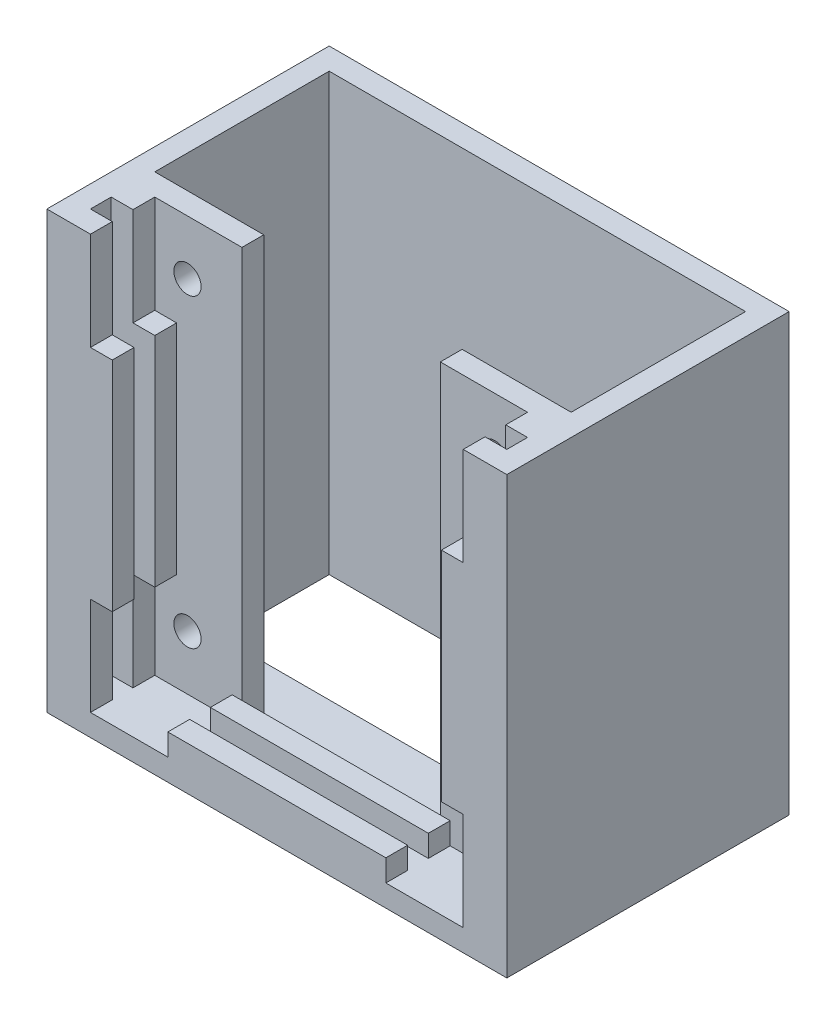
SolidWorks part; units mm, degrees
ref_plane "Front Plane" through (0, 0, 0) normal (0, 0, 1) x (1, 0, 0)
ref_plane "Top Plane" through (0, 0, 0) normal (0, 1, 0) x (1, 0, 0)
ref_plane "Right Plane" through (0, 0, 0) normal (1, 0, 0) x (0, 0, -1)
sketch "Sketch1" plane through (0, 0, 0) normal (0, 1, 0) x (1, 0, 0)
  line L5 (-62.899, -24.1935) -> (-24.699, -24.1935)
  line L6 (-62.899, -24.1935) -> (-62.899, -26.0935)
  line L7 (-62.899, -26.0935) -> (-24.699, -26.0935)
  line L8 (-24.699, -24.1935) -> (-24.699, -26.0935)
  line L9 (-60.899, -22.1935) -> (-26.699, -22.1935)
  line L10 (-60.899, -22.1935) -> (-60.899, -28.0935)
  line L11 (-60.899, -28.0935) -> (-26.699, -28.0935)
  line L12 (-26.699, -22.1935) -> (-26.699, -28.0935)
  line L13 (-64.899, -22.1935) -> (-22.699, -22.1935)
  line L14 (-64.899, -22.1935) -> (-64.899, -28.0935)
  line L15 (-64.899, -28.0935) -> (-22.699, -28.0935)
  line L16 (-22.699, -22.1935) -> (-22.699, -28.0935)
  point P8 (-24.699, -25.1435)
  dimension "D1" = 38.2
  dimension "D2" = 1.9
  dimension "D3" = 2
  dimension "D4" = 2
  dimension "D5" = 2
  dimension "D6" = 2
  dimension "D7" = 2
  dimension "D8" = 2
  dimension "D9" = 2
  dimension "D10" = 2
extrude "Boss-Extrude1" add sketch "Sketch1" along normal blind 38 contours L14 L15 L10 L7 L6 L5 L13 | L16 L13 L12 L5 L8 L7 L15
sketch "Sketch2" plane through (0, 0, 0) normal (0, 1, 0) x (1, 0, 0)
  line L1 (-64.899, -28.0935) -> (-22.699, -28.0935)
  line L2 (-64.899, -28.0935) -> (-64.899, -22.1935)
  line L3 (-64.899, -22.1935) -> (-22.699, -22.1935)
  line L4 (-22.699, -28.0935) -> (-22.699, -22.1935)
  dimension "D1" = 42.2
  dimension "D2" = 5.9
extrude "Boss-Extrude2" add sketch "Sketch2" against normal blind 2
sketch "Sketch3" plane through (0, 0, 22.1935) normal (0, 0, -1) x (-1, 0, 0)
  line L1 (22.699, 38) -> (64.899, 38)
  line L2 (22.699, 38) -> (22.699, -2)
  line L3 (22.699, -2) -> (64.899, -2)
  line L4 (64.899, 38) -> (64.899, -2)
  line L9 (24.699, 38) -> (62.899, 38)
  line L10 (24.699, 38) -> (24.699, 0)
  line L11 (24.699, 0) -> (62.899, 0)
  line L12 (62.899, 38) -> (62.899, 0)
  line M6 (60.899, 38) -> (60.899, 0)
  line M7 (60.899, 0) -> (26.699, 0)
  line M8 (26.699, 0) -> (26.699, 38)
  line M9 (26.699, 38) -> (22.699, 38)
  line M10 (22.699, 38) -> (22.699, -2)
  line M11 (22.699, -2) -> (64.899, -2)
  line M12 (64.899, -2) -> (64.899, 38)
  line M13 (64.899, 38) -> (60.899, 38)
  dimension "D3" = 2
  dimension "D4" = 2
  dimension "D5" = 2
  dimension "D1" = 42.2
  dimension "D2" = 40
extrude "Boss-Extrude3" add sketch "Sketch3" along normal blind 18 contours M13 M6 M7 M8 M9 M10 M11 M12
sketch "Sketch4" plane through (0, 0, 4.1935) normal (0, 0, -1) x (-1, 0, 0)
  line L1 (22.699, 38) -> (64.899, 38)
  line L2 (22.699, 38) -> (22.699, -2)
  line L3 (22.699, -2) -> (64.899, -2)
  line L4 (64.899, 38) -> (64.899, -2)
extrude "Boss-Extrude4" add sketch "Sketch4" along normal blind 2
sketch "Sketch5" plane through (0, 0, 0) normal (0, 1, 0) x (1, 0, 0)
  line L13 (-60.899, -28.0935) -> (-26.699, -28.0935)
  line L14 (-60.899, -28.0935) -> (-60.899, -4.1935)
  line L15 (-26.699, -28.0935) -> (-26.699, -4.1935)
  line L16 (-60.899, -4.1935) -> (-26.699, -4.1935)
  line L18 (-60.899, -16.1435) -> (-26.699, -16.1435)
  line L20 (-62.899, -4.1935) -> (-60.899, -4.1935)
  line L21 (-62.899, -4.1935) -> (-62.899, -16.1435)
  line L22 (-62.899, -16.1435) -> (-60.899, -16.1435)
  line L23 (-60.899, -4.1935) -> (-60.899, -16.1435)
  line L24 (-26.699, -16.1435) -> (-24.699, -16.1435)
  line L25 (-26.699, -16.1435) -> (-26.699, -4.1935)
  line L26 (-26.699, -4.1935) -> (-24.699, -4.1935)
  line L27 (-24.699, -16.1435) -> (-24.699, -4.1935)
  dimension "D1" = 34.2
  dimension "D2" = 23.9
extrude "Cut-Extrude1" cut sketch "Sketch5" against normal through all
sketch "Sketch6" plane through (-60.899, 0, 0) normal (1, 0, 0) x (0, 0, -1)
  line L0 (-28.0935, 19) -> (-22.1935, 19)
  line L1 (-28.0935, 38) -> (-28.0935, 0) construction
  line L2 (-22.1935, 38) -> (-22.1935, 0) construction
  line L4 (-28.0935, 9) -> (-22.1935, 9)
  line L5 (-28.0935, 9) -> (-28.0935, 29)
  line L6 (-28.0935, 29) -> (-22.1935, 29)
  line L7 (-22.1935, 9) -> (-22.1935, 29)
  line L8 (-28.0935, 9) -> (-22.1935, 29) construction
  line L9 (-28.0935, 29) -> (-22.1935, 9) construction
  line L14 (-26.0935, 38) -> (-26.0935, 0) construction
  line L15 (-24.1935, 29) -> (-26.0935, 29)
  line L16 (-24.1935, 29) -> (-24.1935, 9)
  line L17 (-24.1935, 9) -> (-26.0935, 9)
  line L18 (-26.0935, 29) -> (-26.0935, 9)
  line L19 (-24.1935, 29) -> (-26.0935, 9) construction
  line L20 (-24.1935, 9) -> (-26.0935, 29) construction
  point P6 (-25.1435, 19)
  point P11 (-25.1435, 19)
  point P12 (-25.1435, 19)
  line M12 (-26.0935, 0) -> (-26.0935, 38)
  line M14 (-28.0935, 38) -> (-28.0935, 0)
  dimension "D1" = 20
  dimension "D2" = 20
  dimension "D3" = 1.9
extrude "Boss-Extrude5" add sketch "Sketch6" along normal blind 2 contours L6 L0 M14 M12 | L6 L16 L0 L7 | L4 L0 M14 M12 | L0 L16 L4 L7
sketch "Sketch7" plane through (-26.699, 0, 0) normal (-1, 0, 0) x (0, 0, 1)
  line L0 (28.0935, 19) -> (22.1935, 19)
  line L1 (28.0935, 38) -> (28.0935, 0) construction
  line L2 (22.1935, 38) -> (22.1935, 0) construction
  line L3 (24.1935, 38) -> (24.1935, 0) construction
  line L4 (28.0935, 29) -> (22.1935, 29)
  line L5 (28.0935, 29) -> (28.0935, 9)
  line L6 (28.0935, 9) -> (22.1935, 9)
  line L7 (22.1935, 29) -> (22.1935, 9)
  line L8 (28.0935, 29) -> (22.1935, 9) construction
  line L9 (28.0935, 9) -> (22.1935, 29) construction
  line L10 (26.0935, 9) -> (24.1935, 9)
  line L11 (26.0935, 9) -> (26.0935, 29)
  line L12 (26.0935, 29) -> (24.1935, 29)
  line L13 (24.1935, 9) -> (24.1935, 29)
  line L14 (26.0935, 9) -> (24.1935, 29) construction
  line L15 (26.0935, 29) -> (24.1935, 9) construction
  point P6 (25.1435, 19)
  point P11 (25.1435, 19)
  line M5 (28.0935, 0) -> (28.0935, 38)
  line M7 (26.0935, 38) -> (26.0935, 0)
  dimension "D1" = 20
  dimension "D2" = 20
  dimension "D3" = 1.9
extrude "Boss-Extrude6" add sketch "Sketch7" along normal blind 2 contours L4 L0 M5 M7 | L6 L0 M5 M7 | L6 L13 L0 L7 | L0 L13 L4 L7
sketch "Sketch8" plane through (0, 0, 0) normal (0, 1, 0) x (1, 0, 0)
  line L0 (-43.799, -22.1935) -> (-43.799, -28.0935)
  line L1 (-60.899, -28.0935) -> (-26.699, -28.0935)
  line L2 (-60.899, -28.0935) -> (-60.899, -22.1935)
  line L3 (-60.899, -22.1935) -> (-26.699, -22.1935)
  line L4 (-26.699, -28.0935) -> (-26.699, -22.1935)
  line L5 (-60.899, -26.0935) -> (-26.699, -26.0935)
  line L6 (-60.899, -26.0935) -> (-60.899, -24.1935)
  line L7 (-60.899, -24.1935) -> (-26.699, -24.1935)
  line L8 (-26.699, -26.0935) -> (-26.699, -24.1935)
  line L9 (-53.799, -22.1935) -> (-53.799, -28.0935)
  line L10 (-33.799, -28.0935) -> (-33.799, -22.1935)
  line M21 (-60.899, -28.0935) -> (-26.699, -28.0935)
  dimension "D1" = 10
  dimension "D2" = 10
extrude "Boss-Extrude7" add sketch "Sketch8" along normal blind 2 contours L3 L9 L7 L0 | L7 L10 L3 L0 | L5 L9 L1 L0 | L10 L5 L0 M21
sketch "Sketch9" plane through (0, 0, 0) normal (0, 1, 0) x (1, 0, 0)
  line L1 (-62.899, -22.1935) -> (-52.899, -22.1935)
  line L2 (-62.899, -22.1935) -> (-62.899, -20.1935)
  line L3 (-62.899, -20.1935) -> (-52.899, -20.1935)
  line L4 (-52.899, -22.1935) -> (-52.899, -20.1935)
  line L5 (-24.699, -22.1935) -> (-34.699, -22.1935)
  line L6 (-24.699, -22.1935) -> (-24.699, -20.1935)
  line L7 (-24.699, -20.1935) -> (-34.699, -20.1935)
  line L8 (-34.699, -22.1935) -> (-34.699, -20.1935)
  dimension "D3" = 2
  dimension "D4" = 2
  dimension "D1" = 10
  dimension "D2" = 10
extrude "Boss-Extrude8" add sketch "Sketch9" along normal up to surface (38 mm away) contours L2 L1 L4 L3 | L6 L5 L8 L7 up to face at (-43.799, 38, 20.7535)
hole_wizard "M3x0.5 Tapped Hole1" positions "3DSketch1" profile "Sketch10" tap size "M3x0.5" standard "ANSI Metric"
sketch3d "3DSketch1"
  line L0 (-62.899, 38, 20.1935) -> (-62.899, 0, 20.1935) construction
  line L1 (-62.899, 38, 20.1935) -> (-52.899, 38, 20.1935) construction
  line L2 (-62.899, 0, 20.1935) -> (-52.899, 0, 20.1935) construction
  point P0 (-57.899, 33, 20.1935)
  point P2 (-57.899, 5, 20.1935)
  dimension "D1" = 5
  dimension "D2" = 5
  dimension "D3" = 5
  dimension "D4" = 5
sketch "Sketch10" plane through (-57.899, 33, 20.1935) normal (1, 0, 0) x (0, 1, 0)
  line L0 (0, 0) -> (0, 7.9)
  line L1 (0, 7.9) -> (1.25, 7.9)
  line L2 (1.25, 7.9) -> (1.25, 0)
  line L5 (1.25, 0) -> (0, 0)
  line L11 (0, -6.35) -> (0, 107.95) construction
  dimension "Thread Major Dia." = 2.5
  dimension "Thru Tap Drill Depth" = 7.9
hole_wizard "M3x0.5 Tapped Hole2" positions "3DSketch2" profile "Sketch11" tap size "M3x0.5" standard "ANSI Metric"
sketch3d "3DSketch2"
  line L0 (-24.699, 38, 20.1935) -> (-34.699, 38, 20.1935) construction
  line L1 (-24.699, 38, 20.1935) -> (-24.699, 0, 20.1935) construction
  line L2 (-24.699, 0, 20.1935) -> (-34.699, 0, 20.1935) construction
  point P0 (-29.699, 33, 20.1935)
  point P2 (-29.699, 5, 20.1935)
  dimension "D1" = 5
  dimension "D2" = 5
  dimension "D3" = 5
  dimension "D4" = 5
sketch "Sketch11" plane through (-29.699, 33, 20.1935) normal (1, 0, 0) x (0, 1, 0)
  line L0 (0, 0) -> (0, 7.9)
  line L1 (0, 7.9) -> (1.25, 7.9)
  line L2 (1.25, 7.9) -> (1.25, 0)
  line L5 (1.25, 0) -> (0, 0)
  line L11 (0, -6.35) -> (0, 107.95) construction
  dimension "Thread Major Dia." = 2.5
  dimension "Thru Tap Drill Depth" = 7.9
equation "\"camera side length\"= 38"
equation "\"camera module panel thickness\"=1.7"
equation "\"tolerance\"= 0.1"
equation "\"D1@Sketch1\"= \"camera side length\" + \"tolerance\" * 2"
equation "\"D2@Sketch1\"=\"camera module panel thickness\"+\"tolerance\"*2"
equation "\"camera module side clearance\"= 2"
equation "\"camera mount thickness\"= 2"
equation "\"D3@Sketch1\"=\"camera mount thickness\""
equation "\"D4@Sketch1\"=\"camera mount thickness\""
equation "\"D5@Sketch1\"=\"camera module side clearance\""
equation "\"D6@Sketch1\"=\"camera module side clearance\""
equation "\"D7@Sketch1\"=\"camera mount thickness\""
equation "\"D8@Sketch1\"=\"camera mount thickness\""
equation "\"D9@Sketch1\"=\"camera mount thickness\""
equation "\"D10@Sketch1\"=\"camera mount thickness\""
equation "\"D1@Boss-Extrude1\"=\"camera side length\""
equation "\"D1@Boss-Extrude2\"=\"camera mount thickness\""
equation "\"camera module hole offset\" = 5"
equation "\"camera module hole diameter\"= 2.33"
equation "\"camera mount inner depth\"= 20"
equation "\"D1@Boss-Extrude3\"=\"camera mount inner depth\"-\"camera mount thickness\""
equation "\"D1@Boss-Extrude4\"=\"camera mount thickness\""
equation "\"D3@Sketch3\"=\"camera mount thickness\""
equation "\"D4@Sketch3\"=\"camera mount thickness\""
equation "\"D5@Sketch3\"=\"camera mount thickness\""
equation "\"D2@Sketch5\"=\"camera mount thickness\"+\"tolerance\"*2+\"camera module panel thickness\"+\"camera mount inner depth\""
equation "\"mount protrusion length\"=20"
equation "\"D1@Sketch6\"=\"mount protrusion length\""
equation "\"mount protrusion depth\"=2"
equation "\"D1@Boss-Extrude5\"=\"mount protrusion depth\""
equation "\"D1@Sketch7\"=\"mount protrusion length\""
equation "\"D1@Boss-Extrude6\"=\"mount protrusion depth\""
equation "\"D1@Sketch8\"=\"mount protrusion length\"/2"
equation "\"D2@Sketch8\"=\"mount protrusion length\"/2"
equation "\"D1@Boss-Extrude7\"=\"mount protrusion depth\""
equation "\"hole pane length\"=10"
equation "\"D1@Sketch9\"=\"hole pane length\""
equation "\"D2@Sketch9\"=\"hole pane length\""
equation "\"D3@Sketch9\"=\"camera mount thickness\""
equation "\"D4@Sketch9\"=\"camera mount thickness\""
equation "\"D1@3DSketch1\"=\"camera module hole offset\""
equation "\"D2@3DSketch1\"=\"camera module hole offset\""
equation "\"D3@3DSketch1\"=\"camera module hole offset\""
equation "\"D4@3DSketch1\"=\"camera module hole offset\""
equation "\"D1@3DSketch2\"=\"camera module hole offset\""
equation "\"D2@3DSketch2\"=\"camera module hole offset\""
equation "\"D3@3DSketch2\"=\"camera module hole offset\""
equation "\"D4@3DSketch2\"=\"camera module hole offset\""
